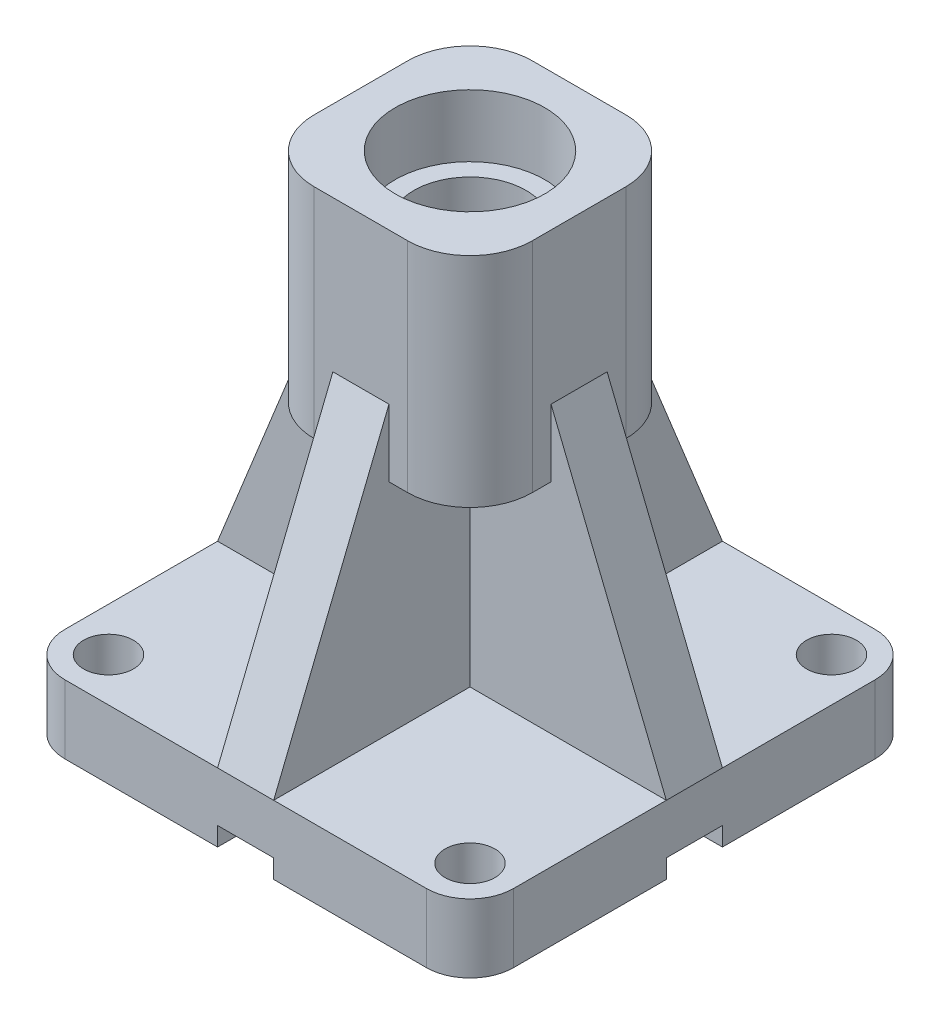
SolidWorks part; units mm, degrees
ref_plane "정면" through (0, 0, 0) normal (0, 0, 1) x (1, 0, 0)
ref_plane "윗면" through (0, 0, 0) normal (0, 1, 0) x (1, 0, 0)
ref_plane "우측면" through (0, 0, 0) normal (1, 0, 0) x (0, 0, -1)
sketch "스케치1" plane through (0, 0, 0) normal (0, 1, 0) x (1, 0, 0)
  line L1 (-29, 36) -> (29, 36)
  line L2 (-36, 29) -> (-36, -29)
  line L3 (-29, -36) -> (29, -36)
  line L4 (36, 29) -> (36, -29)
  line L5 (-36, 36) -> (36, -36) construction
  line L6 (-36, -36) -> (36, 36) construction
  arc A0 (29, 36) -> (36, 29) centre (29, 29) cw
  arc A1 (-36, -29) -> (-29, -36) centre (-29, -29) ccw
  arc A2 (-29, 36) -> (-36, 29) centre (-29, 29) ccw
  arc A3 (29, -36) -> (36, -29) centre (29, -29) ccw
  point P0 (0, 0)
  dimension "D3" = 7
  dimension "D1" = 72
  dimension "D2" = 72
extrude "보스-돌출1" add sketch "스케치1" along normal blind 11
sketch "스케치2" plane through (0, 0, 0) normal (0, 0, 1) x (1, 0, 0)
  line L0 (-36, 11) -> (-13.6512, 66.3153)
  line L1 (-13.6512, 66.3153) -> (13.6512, 66.3153)
  line L2 (13.6512, 66.3153) -> (36, 11)
  line L3 (36, 11) -> (-36, 11)
  dimension "D1" = 68
  dimension "D2" = 68
extrude "보스-돌출2" add sketch "스케치2" along normal mid plane 9
sketch "스케치3" plane through (0, 0, 0) normal (1, 0, 0) x (0, 0, -1)
  line L0 (-36, 11) -> (-13.6512, 66.3153)
  line L1 (-13.6512, 66.3153) -> (13.6512, 66.3153)
  line L2 (13.6512, 66.3153) -> (36, 11)
  line L3 (36, 11) -> (-36, 11)
  line L4 (-4.5, 66.3153) -> (4.5, 66.3153) construction
  dimension "D1" = 68
  dimension "D2" = 68
extrude "보스-돌출3" add sketch "스케치3" along normal mid plane 9
ref_plane "평면1" through (0, 81, 0) normal (0, 1, 0) x (1, 0, 0)
sketch "스케치4" plane through (0, 81, 0) normal (0, 1, 0) x (1, 0, 0)
  line L1 (-7.5, 17.5) -> (7.5, 17.5)
  line L2 (-17.5, 7.5) -> (-17.5, -7.5)
  line L3 (-7.5, -17.5) -> (7.5, -17.5)
  line L4 (17.5, 7.5) -> (17.5, -7.5)
  line L5 (-17.5, 17.5) -> (17.5, -17.5) construction
  line L6 (-17.5, -17.5) -> (17.5, 17.5) construction
  arc A0 (7.5, 17.5) -> (17.5, 7.5) centre (7.5, 7.5) cw
  arc A1 (-17.5, -7.5) -> (-7.5, -17.5) centre (-7.5, -7.5) ccw
  arc A2 (-7.5, 17.5) -> (-17.5, 7.5) centre (-7.5, 7.5) ccw
  arc A3 (7.5, -17.5) -> (17.5, -7.5) centre (7.5, -7.5) ccw
  point P0 (0, 0)
  dimension "D3" = 10
  dimension "D1" = 35
  dimension "D2" = 35
extrude "보스-돌출4" add sketch "스케치4" against normal blind 35
hole_wizard "M4 소켓 머리 캡 나사용 카운터보어1" positions "스케치10" profile "스케치11" counterbore size "M4" standard "KS"
sketch "스케치10" plane through (0, 81, 0) normal (0, 1, 0) x (1, 0, 0)
  point P0 (0, 0)
sketch "스케치11" plane through (0, 81, 0) normal (1, 0, 0) x (0, 0, 1)
  line L0 (0, 0) -> (0, 25.4077)
  line L1 (0, 25.4077) -> (9, 20)
  line L2 (9, 20) -> (9, 10)
  line L3 (9, 10) -> (12, 10)
  line L4 (12, 10) -> (12, 0)
  line L5 (12, 0) -> (0, 0)
  line L10 (0, 25.4077) -> (-9, 20) construction
  line L11 (0, -6.35) -> (0, 107.95) construction
  dimension "구멍 지름" = 18
  dimension "구멍 깊이" = 20
  dimension "카운터보어 지름" = 24
  dimension "카운터보어 깊이" = 10
  dimension "드릴 각도" = 118
sketch "스케치14" plane through (0, 0, 0) normal (0, -1, 0) x (1, 0, 0)
  circle A1 centre (-29, 29) radius 4
  circle A2 centre (29, 29) radius 4
  circle A3 centre (-29, -29) radius 4
  circle A4 centre (29, -29) radius 4
extrude "컷-돌출1" cut sketch "스케치14" against normal blind 15
sketch "스케치15" plane through (0, 0, 0) normal (1, 0, 0) x (0, 0, -1)
  line L1 (-4.5, 3) -> (4.5, 3)
  line L2 (-4.5, 3) -> (-4.5, 0)
  line L3 (-4.5, 0) -> (4.5, 0)
  line L4 (4.5, 3) -> (4.5, 0)
  point P4 (0, 0)
  dimension "D1" = 3
  dimension "D2" = 9
extrude "컷-돌출2" cut sketch "스케치15" against normal through all both and the other way through all
sketch "스케치16" plane through (0, 0, 0) normal (0, 0, 1) x (1, 0, 0)
  line L0 (-29, 0) -> (29, 0) construction
  line L1 (-4.5, 3) -> (4.5, 3)
  line L2 (-4.5, 3) -> (-4.5, 0)
  line L3 (-4.5, 0) -> (4.5, 0)
  line L4 (4.5, 3) -> (4.5, 0)
  point P6 (0, 0)
  dimension "D1" = 9
  dimension "D2" = 3
extrude "컷-돌출3" cut sketch "스케치16" against normal through all both and the other way through all
